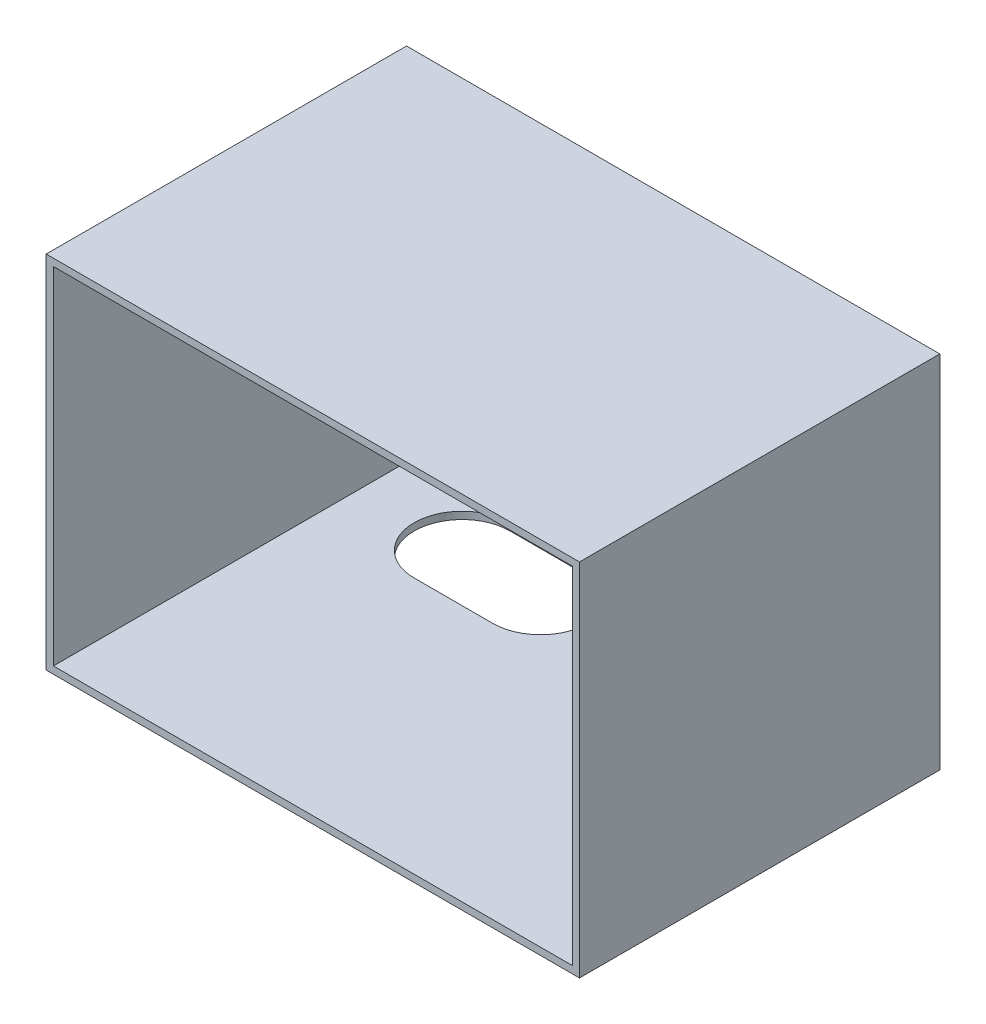
SolidWorks part; units mm, degrees
ref_plane "Front Plane" through (0, 0, 0) normal (0, 0, 1) x (1, 0, 0)
ref_plane "Top Plane" through (0, 0, 0) normal (0, 1, 0) x (1, 0, 0)
ref_plane "Right Plane" through (0, 0, 0) normal (1, 0, 0) x (0, 0, -1)
sketch "Sketch1" plane through (0, 0, 0) normal (0, 0, 1) x (1, 0, 0)
  line L1 (0, 0) -> (187.96, 0)
  line L2 (0, 0) -> (0, 127)
  line L3 (0, 127) -> (187.96, 127)
  line L4 (187.96, 0) -> (187.96, 127)
  dimension "D1" = 187.96
extrude "Boss-Extrude1" add sketch "Sketch1" along normal blind 127
sketch "Sketch3" plane through (0, 0, 0) normal (0, 0, -1) x (-1, 0, 0)
  line L1 (0, 0) -> (-187.96, 0) construction
  line L2 (-170.18, 0) -> (-132.08, 0)
  line L4 (-140.9292, 25.4124) -> (-132.08, 0)
  line L5 (-140.9292, 25.4124) -> (-161.1501, 25.4124)
  line L6 (-161.1501, 25.4124) -> (-170.18, 0)
  dimension "D2" = 38.1
extrude "Cut-Extrude1" cut sketch "Sketch3" against normal blind 25.4
sketch "Sketch6" plane through (0, 25.4124, 0) normal (0, -1, 0) x (1, 0, 0)
  circle A0 centre (151.0397, 7.3914) radius 4.699
  dimension "D1" = 9.398
extrude "Cut-Extrude2" cut sketch "Sketch6" against normal blind 12.7
sketch "Sketch7" plane through (0, 0, 127) normal (0, 0, 1) x (1, 0, 0)
  line L14 (185.42, 2.54) -> (185.42, 124.46)
  line L15 (2.54, 2.54) -> (185.42, 2.54)
  line L16 (2.54, 124.46) -> (2.54, 2.54)
  line L17 (185.42, 124.46) -> (2.54, 124.46)
  line L18 (185.42, 2.54) -> (185.42, 124.46)
  line L19 (2.54, 2.54) -> (185.42, 2.54)
  line L20 (2.54, 124.46) -> (2.54, 2.54)
  line L21 (185.42, 124.46) -> (2.54, 124.46)
  dimension "D1" = 2.54
extrude "Cut-Extrude4" cut sketch "Sketch7" against normal offset from surface (99.06 mm away) 2.54 up to face at (151.0848, 12.7062, 25.4)
sketch "Sketch9" plane through (0, 0, 27.94) normal (0, 0, 1) x (1, 0, 0)
  line L24 (162.9432, 27.9524) -> (171.973, 2.54)
  line L25 (139.1241, 27.9524) -> (162.9432, 27.9524)
  line L26 (130.2749, 2.54) -> (139.1241, 27.9524)
  line L27 (2.54, 2.54) -> (130.2749, 2.54)
  line L28 (2.54, 124.46) -> (2.54, 2.54)
  line L29 (185.42, 124.46) -> (2.54, 124.46)
  line L30 (185.42, 2.54) -> (185.42, 124.46)
  line L31 (171.973, 2.54) -> (185.42, 2.54)
  line L32 (162.9432, 27.9524) -> (171.973, 2.54)
  line L33 (139.1241, 27.9524) -> (162.9432, 27.9524)
  line L34 (130.2749, 2.54) -> (139.1241, 27.9524)
  line L35 (2.54, 2.54) -> (130.2749, 2.54)
  line L36 (2.54, 124.46) -> (2.54, 2.54)
  line L37 (185.42, 124.46) -> (2.54, 124.46)
  line L38 (185.42, 2.54) -> (185.42, 124.46)
  line L39 (171.973, 2.54) -> (185.42, 2.54)
  dimension "D1" = 2.54
extrude "Cut-Extrude5" cut sketch "Sketch9" against normal offset from surface (25.4 mm away) 2.54 up to face at (122.5324, 38.1031, 0)
sketch "Sketch10" plane through (0, 0, 0) normal (0, -1, 0) x (1, 0, 0)
  line L1 (0, 0) -> (132.08, 0) construction
  line L2 (39.2818, 19.685) -> (66.929, 19.685) construction
  line L3 (39.2818, 36.576) -> (66.929, 36.576)
  line L4 (39.2818, 2.794) -> (66.929, 2.794)
  line L6 (132.08, 25.4) -> (132.08, 0) construction
  arc A0 (39.2818, 36.576) -> (39.2818, 2.794) centre (39.2818, 19.685) ccw
  arc A1 (66.929, 2.794) -> (66.929, 36.576) centre (66.929, 19.685) ccw
  point P7 (53.1054, 19.685)
  point P12 (83.82, 19.685)
  dimension "D1" = 48.26
  dimension "D3" = 33.782
  dimension "D4" = 2.794
extrude "Cut-Extrude6" cut sketch "Sketch10" against normal blind 3.048
